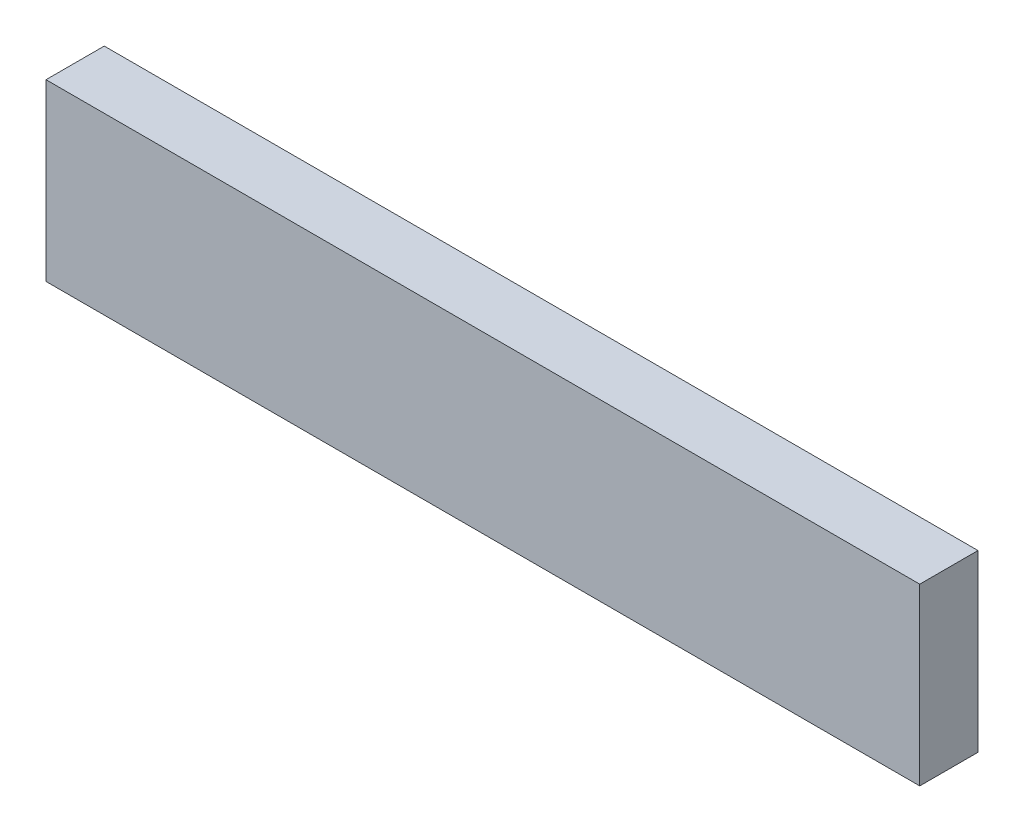
SolidWorks part; units mm, degrees
ref_plane "前视基准面" through (0, 0, 0) normal (0, 0, 1) x (1, 0, 0)
ref_plane "上视基准面" through (0, 0, 0) normal (0, 1, 0) x (1, 0, 0)
ref_plane "右视基准面" through (0, 0, 0) normal (1, 0, 0) x (0, 0, -1)
other "Configuration Table"
sketch "草图1" plane through (0, 0, 0) normal (0, 0, 1) x (1, 0, 0)
  line L1 (-150, -30) -> (150, -30)
  line L2 (-150, -30) -> (-150, 30)
  line L3 (-150, 30) -> (150, 30)
  line L4 (150, -30) -> (150, 30)
  line L5 (-150, -30) -> (150, 30) construction
  line L6 (-150, 30) -> (150, -30) construction
  point P0 (0, 0)
extrude "凸台-拉伸1" add sketch "草图1" along normal blind 20
